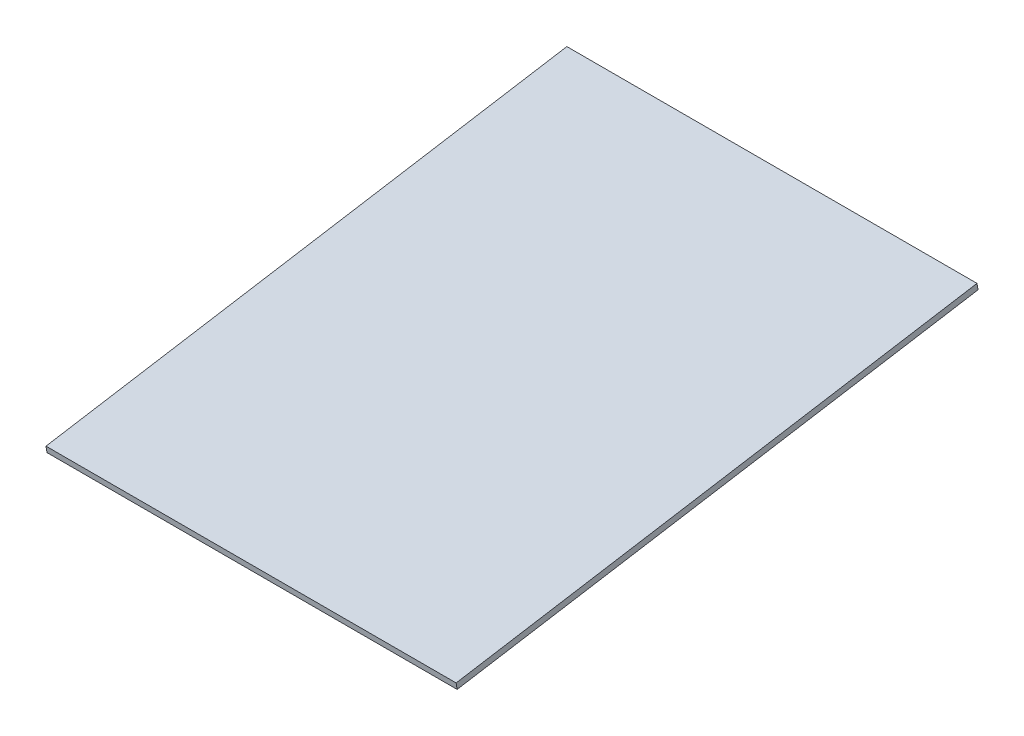
SolidWorks part; units mm, degrees
ref_plane "Front Plane" through (0, 0, 0) normal (0, 0, 1) x (1, 0, 0)
ref_plane "Top Plane" through (0, 0, 0) normal (0, 1, 0) x (1, 0, 0)
ref_plane "Right Plane" through (0, 0, 0) normal (1, 0, 0) x (0, 0, -1)
sketch "Sketch1" plane through (0, 543.8762, 89.3847) normal (0, 0.9868, 0.1622) x (1, 0, 0)
  line L0 (100, -954.2422) -> (-100, -954.2422) construction
  line L1 (100, -954.2422) -> (100, -1224.0672) construction
  line L2 (100, -1224.0672) -> (-100, -1224.0672) construction
  line L4 (100, -954.2422) -> (-100, -954.2422)
  line L5 (100, -954.2422) -> (100, -1224.0672)
  line L6 (100, -1224.0672) -> (-100, -1224.0672)
  line L8 (-109.652, -954.2422) -> (-100, -954.2422) construction
  line L9 (-109.652, -1224.0672) -> (-109.652, -954.2422) construction
  line L10 (-100, -1224.0672) -> (-109.652, -1224.0672) construction
  line L11 (-109.652, -954.2422) -> (-100, -954.2422)
  line L12 (-109.652, -1224.0672) -> (-109.652, -954.2422)
  line L13 (-100, -1224.0672) -> (-109.652, -1224.0672)
extrude "Boss-Extrude1" add sketch "Sketch1" against normal up to vertex (3.175 mm away) from vertex at 0
